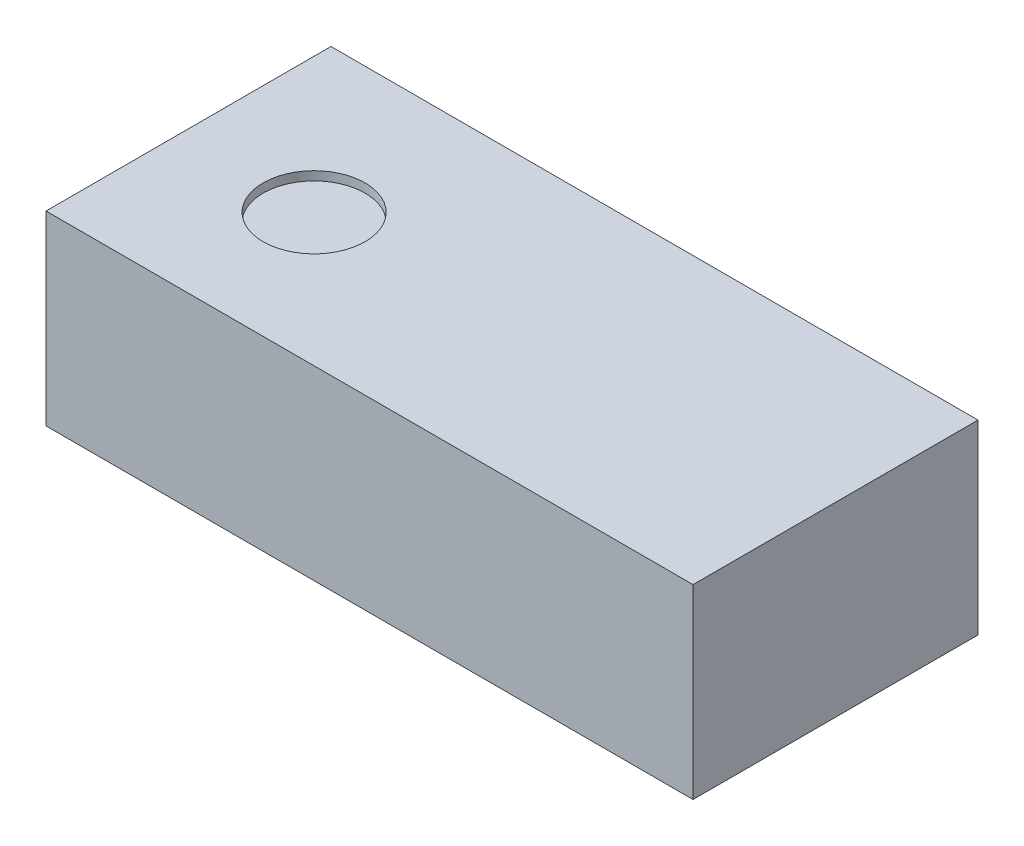
SolidWorks part; units mm, degrees
ref_plane "Front Plane" through (0, 0, 0) normal (0, 0, 1) x (1, 0, 0)
ref_plane "Top Plane" through (0, 0, 0) normal (0, 1, 0) x (1, 0, 0)
ref_plane "Right Plane" through (0, 0, 0) normal (1, 0, 0) x (0, 0, -1)
sketch "Sketch1" plane through (0, 0, 0) normal (0, 1, 0) x (1, 0, 0)
  line L1 (-36.5, 16.075) -> (36.5, 16.075)
  line L2 (-36.5, 16.075) -> (-36.5, -16.075)
  line L3 (-36.5, -16.075) -> (36.5, -16.075)
  line L4 (36.5, 16.075) -> (36.5, -16.075)
  line L5 (-36.5, 16.075) -> (36.5, -16.075) construction
  line L6 (-36.5, -16.075) -> (36.5, 16.075) construction
  point P0 (0, 0)
  dimension "D1" = 73
  dimension "D2" = 32.15
extrude "Boss-Extrude1" add sketch "Sketch1" along normal blind 21
sketch "Sketch2" plane through (0, 21, 0) normal (0, 1, 0) x (1, 0, 0)
  line L0 (-36.5, 16.075) -> (-36.5, -16.075) construction
  line L1 (-36.5, -16.075) -> (36.5, -16.075) construction
  circle A0 centre (-21.25, -1.075) radius 5.75
  dimension "D1" = 11.5
  dimension "D2" = 15.25
  dimension "D3" = 15
extrude "Cut-Extrude1" cut sketch "Sketch2" against normal blind 1
equation "\"D2@Sketch2\"=9.5+(11.5/2)"
